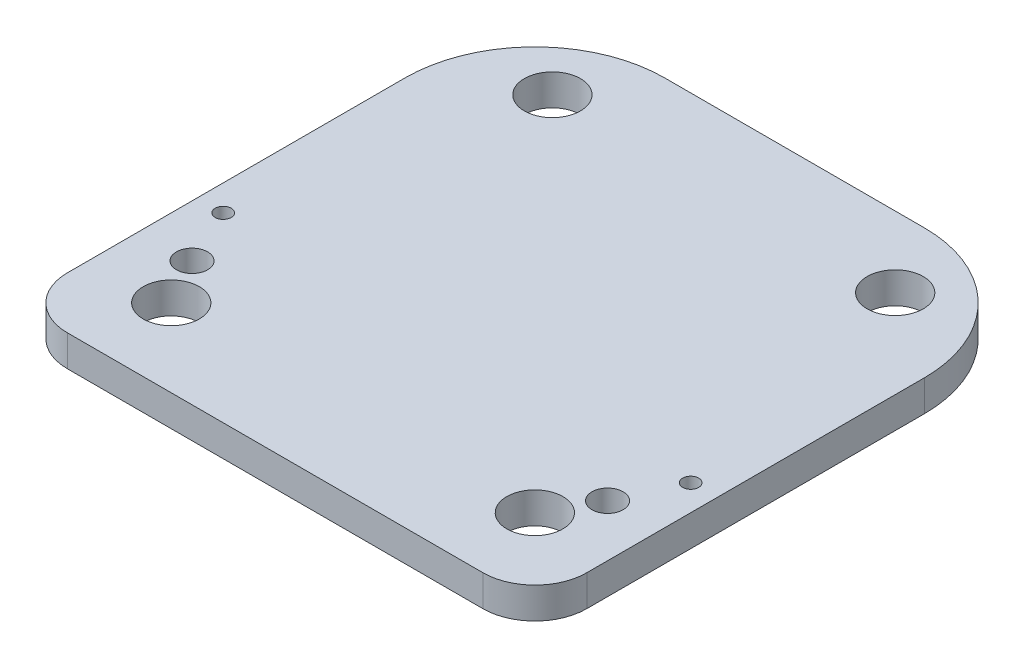
SolidWorks part; units mm, degrees
ref_plane "Płaszczyzna przednia" through (0, 0, 0) normal (0, 0, 1) x (1, 0, 0)
ref_plane "Płaszczyzna górna" through (0, 0, 0) normal (0, 1, 0) x (1, 0, 0)
ref_plane "Płaszczyzna prawa" through (0, 0, 0) normal (1, 0, 0) x (0, 0, -1)
sketch "Szkic1" plane through (0, 0, 0) normal (0, 1, 0) x (1, 0, 0)
  line L8 (10, 0) -> (90, 0)
  line L9 (100, 10) -> (100, 75)
  line L10 (75, 100) -> (25, 100)
  line L11 (0, 75) -> (0, 10)
  arc A8 (90, 0) -> (100, 10) centre (90, 10) ccw
  arc A9 (100, 75) -> (75, 100) centre (75, 75) ccw
  arc A10 (25, 100) -> (0, 75) centre (25, 75) ccw
  arc A11 (0, 10) -> (10, 0) centre (10, 10) ccw
extrude "Dodanie-wyciągnięcie1" add sketch "Szkic1" against normal blind 6
sketch "Szkic2" plane through (0, 0, 0) normal (0, 1, 0) x (1, 0, 0)
  circle A0 centre (17, 86.3783) radius 5.4 construction
  circle A2 centre (15, 15) radius 5.4 construction
  circle A4 centre (17, 86.3783) radius 5.4
  circle A5 centre (83, 86.3783) radius 5.4
  circle A6 centre (15, 15) radius 5.4
  circle A7 centre (85, 15) radius 5.4
extrude "Wytnij-wyciągnięcie1" cut sketch "Szkic2" against normal through all
sketch "Szkic3" plane through (0, -6, 0) normal (0, -1, 0) x (1, 0, 0)
  circle A2 centre (5, -35) radius 1.55 construction
  circle A3 centre (95, -35) radius 1.55 construction
  circle A4 centre (5, -35) radius 1.55
  circle A5 centre (95, -35) radius 1.55
extrude "Wytnij-wyciągnięcie2" cut sketch "Szkic3" against normal through all
sketch "Szkic4" plane through (0, 0, 0) normal (0, 1, 0) x (1, 0, 0)
  circle A2 centre (90, 24) radius 3
  circle A3 centre (10, 24) radius 3
  dimension "D1" = 6
  dimension "D2" = 6
extrude "Wytnij-wyciągnięcie3" cut sketch "Szkic4" against normal through all
